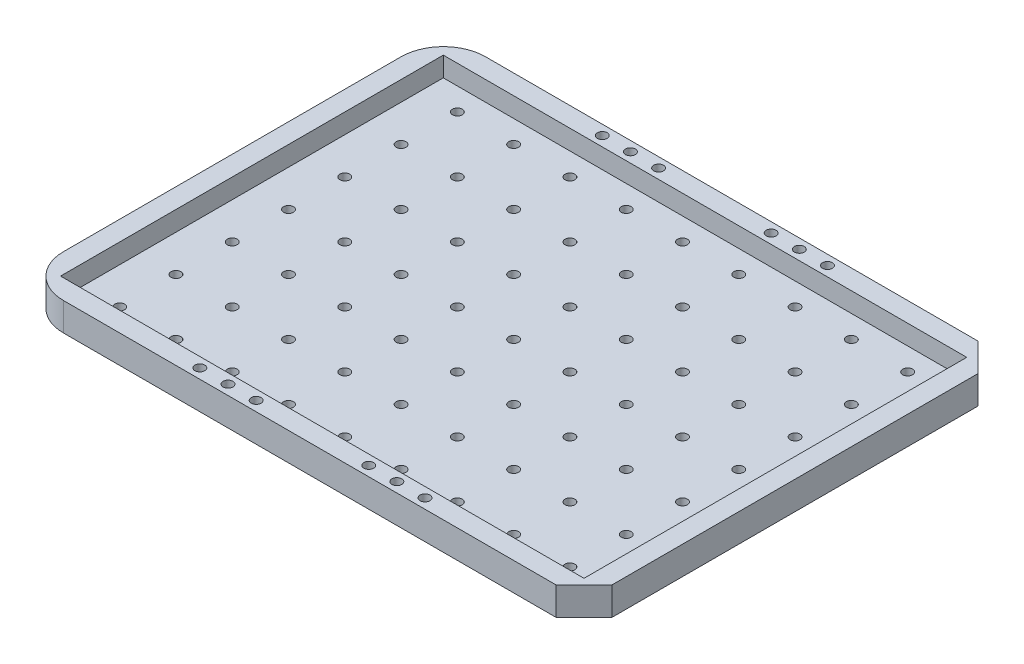
SolidWorks part; units mm, degrees
ref_plane "Front Plane" through (0, 0, 0) normal (0, 0, 1) x (1, 0, 0)
ref_plane "Top Plane" through (0, 0, 0) normal (0, 1, 0) x (1, 0, 0)
ref_plane "Right Plane" through (0, 0, 0) normal (1, 0, 0) x (0, 0, -1)
sketch "Sketch1" plane through (0, 0, 0) normal (0, 1, 0) x (1, 0, 0)
  line L1 (0, 0) -> (200, 0)
  line L2 (0, 0) -> (0, 150)
  line L3 (0, 150) -> (200, 150)
  line L4 (200, 0) -> (200, 150)
  dimension "D1" = 200
  dimension "D2" = 150
extrude "Chasis" add sketch "Sketch1" along normal blind 10
sketch "Sketch2" plane through (0, 10, 0) normal (0, 1, 0) x (1, 0, 0)
  line L0 (0, 150) -> (0, 0) construction
  line L1 (7, 143) -> (193, 143)
  line L2 (7, 143) -> (7, 7)
  line L3 (7, 7) -> (193, 7)
  line L4 (193, 143) -> (193, 7)
  line L5 (200, 0) -> (200, 150) construction
  line L6 (200, 150) -> (0, 150) construction
  line L7 (0, 0) -> (200, 0) construction
  dimension "D1" = 7
  dimension "D2" = 7
  dimension "D3" = 7
  dimension "D4" = 7
extrude "Chasis Edge" cut sketch "Sketch2" against normal blind 7
sketch "Hole Pattern" plane through (0, 3, 0) normal (0, 1, 0) x (1, 0, 0)
  line L0 (7, 143) -> (7, 7) construction
  line L1 (193, 143) -> (7, 143) construction
  line L2 (193, 7) -> (193, 143) construction
  line L3 (7, 7) -> (193, 7) construction
  circle A0 centre (20, 135) radius 1.75
  circle A1 centre (40, 135) radius 1.75
  circle A2 centre (60, 135) radius 1.75
  circle A3 centre (80, 135) radius 1.75
  circle A4 centre (100, 135) radius 1.75
  circle A5 centre (120, 135) radius 1.75
  circle A6 centre (140, 135) radius 1.75
  circle A7 centre (160, 135) radius 1.75
  circle A8 centre (180, 135) radius 1.75
  circle A9 centre (20, 115) radius 1.75
  circle A10 centre (40, 115) radius 1.75
  circle A11 centre (60, 115) radius 1.75
  circle A12 centre (80, 115) radius 1.75
  circle A13 centre (100, 115) radius 1.75
  circle A14 centre (120, 115) radius 1.75
  circle A15 centre (140, 115) radius 1.75
  circle A16 centre (160, 115) radius 1.75
  circle A17 centre (180, 115) radius 1.75
  circle A18 centre (20, 95) radius 1.75
  circle A19 centre (40, 95) radius 1.75
  circle A20 centre (60, 95) radius 1.75
  circle A21 centre (80, 95) radius 1.75
  circle A22 centre (100, 95) radius 1.75
  circle A23 centre (120, 95) radius 1.75
  circle A24 centre (140, 95) radius 1.75
  circle A25 centre (160, 95) radius 1.75
  circle A26 centre (180, 95) radius 1.75
  circle A27 centre (20, 75) radius 1.75
  circle A28 centre (40, 75) radius 1.75
  circle A29 centre (60, 75) radius 1.75
  circle A30 centre (80, 75) radius 1.75
  circle A31 centre (100, 75) radius 1.75
  circle A32 centre (120, 75) radius 1.75
  circle A33 centre (140, 75) radius 1.75
  circle A34 centre (160, 75) radius 1.75
  circle A35 centre (180, 75) radius 1.75
  circle A36 centre (20, 55) radius 1.75
  circle A37 centre (40, 55) radius 1.75
  circle A38 centre (60, 55) radius 1.75
  circle A39 centre (80, 55) radius 1.75
  circle A40 centre (100, 55) radius 1.75
  circle A41 centre (120, 55) radius 1.75
  circle A42 centre (140, 55) radius 1.75
  circle A43 centre (160, 55) radius 1.75
  circle A44 centre (180, 55) radius 1.75
  circle A45 centre (20, 35) radius 1.75
  circle A46 centre (40, 35) radius 1.75
  circle A47 centre (60, 35) radius 1.75
  circle A48 centre (80, 35) radius 1.75
  circle A49 centre (100, 35) radius 1.75
  circle A50 centre (120, 35) radius 1.75
  circle A51 centre (140, 35) radius 1.75
  circle A52 centre (160, 35) radius 1.75
  circle A53 centre (180, 35) radius 1.75
  circle A54 centre (20, 15) radius 1.75
  circle A55 centre (40, 15) radius 1.75
  circle A56 centre (60, 15) radius 1.75
  circle A57 centre (80, 15) radius 1.75
  circle A58 centre (100, 15) radius 1.75
  circle A59 centre (120, 15) radius 1.75
  circle A60 centre (140, 15) radius 1.75
  circle A61 centre (160, 15) radius 1.75
  circle A62 centre (180, 15) radius 1.75
  dimension "D1" = 3.5
  dimension "D2" = 13
  dimension "D3" = 8
  dimension "D5" = 13
  dimension "D7" = 8
  dimension "D4" = 9
  dimension "D6" = 7
extrude "General Purpose Holes" cut sketch "Hole Pattern" against normal through all
sketch "Sketch16" plane through (0, 10, 0) normal (0, 1, 0) x (1, 0, 0)
  line L0 (130, 150) -> (130, 0) construction
  line L1 (200, 150) -> (0, 150) construction
  line L2 (0, 0) -> (200, 0) construction
  line L3 (70, 150) -> (70, 0) construction
  line L5 (100, 150) -> (100, 0) construction
  line L6 (200, 75) -> (0, 75) construction
  line L7 (200, 0) -> (200, 150) construction
  line L8 (0, 150) -> (0, 0) construction
  circle A0 centre (140, 135) radius 1.75 construction
  circle A1 centre (120, 135) radius 1.75 construction
  circle A2 centre (80, 135) radius 1.75 construction
  circle A3 centre (60, 135) radius 1.75 construction
  circle A4 centre (130, 146.5) radius 1.75
  circle A5 centre (120, 146.5) radius 1.75
  circle A6 centre (140, 146.5) radius 1.75
  circle A7 centre (140, 3.5) radius 1.75
  circle A8 centre (120, 3.5) radius 1.75
  circle A9 centre (130, 3.5) radius 1.75
  circle A10 centre (70, 3.5) radius 1.75
  circle A11 centre (80, 3.5) radius 1.75
  circle A12 centre (60, 3.5) radius 1.75
  circle A13 centre (60, 146.5) radius 1.75
  circle A14 centre (80, 146.5) radius 1.75
  circle A15 centre (70, 146.5) radius 1.75
  dimension "D1" = 3.5
  dimension "D3" = 3.5
  dimension "D4" = 10
  dimension "D5" = 10
  dimension "D6" = 2
  dimension "D2" = 2
extrude "Cut-Extrude4" cut sketch "Sketch16" against normal through all
chamfer "Chamfer2" distance 10 angle 45 2 edges at (200, 5, 0) (200, 5, -150)
fillet "Fillet2" radius 15 2 edges at (0, 5, -150) (0, 5, 0)
